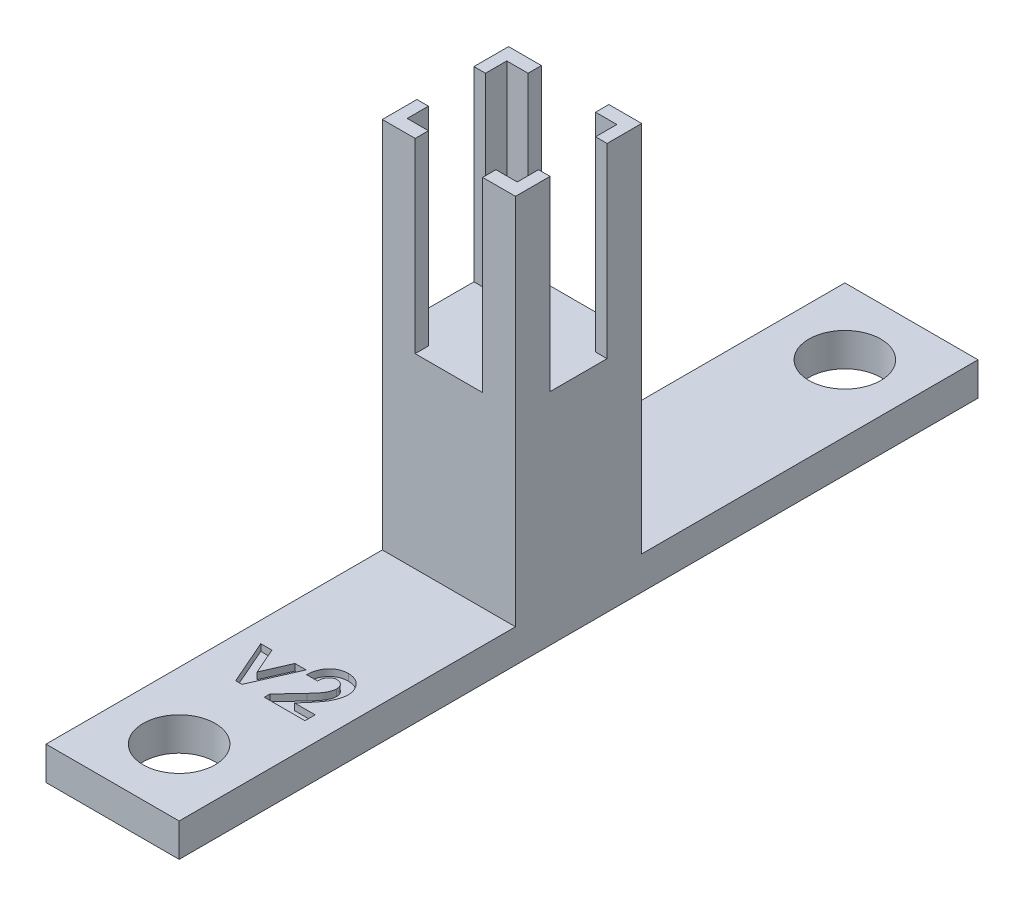
SolidWorks part; units mm, degrees
ref_plane "Front Plane" through (0, 0, 0) normal (0, 0, 1) x (1, 0, 0)
ref_plane "Top Plane" through (0, 0, 0) normal (0, 1, 0) x (1, 0, 0)
ref_plane "Right Plane" through (0, 0, 0) normal (1, 0, 0) x (0, 0, -1)
sketch "Sketch1" plane through (0, 0, 0) normal (0, 1, 0) x (1, 0, 0)
  line L0 (-5.25, 4.75) -> (-5.25, 2.718)
  line L1 (-5.25, -4.75) -> (5.25, -4.75) construction
  line L2 (-5.25, -4.75) -> (-5.25, 4.75) construction
  line L3 (-5.25, 4.75) -> (5.25, 4.75) construction
  line L4 (5.25, -4.75) -> (5.25, 4.75) construction
  line L5 (-5.25, -4.75) -> (5.25, 4.75) construction
  line L6 (-5.25, 4.75) -> (5.25, -4.75) construction
  line L7 (-5.25, 2.718) -> (-6.52, 2.718)
  line L8 (-6.52, 2.718) -> (-6.52, 6.02)
  line L9 (-6.52, 6.02) -> (-3.218, 6.02)
  line L10 (-3.218, 6.02) -> (-3.218, 4.75)
  line L11 (-3.218, 4.75) -> (-5.25, 4.75)
  line L12 (0, 4.75) -> (0, -4.75) construction
  line L13 (-5.25, 0) -> (5.25, 0) construction
  line L14 (6.52, 2.718) -> (6.52, 6.02)
  line L15 (5.25, 2.718) -> (6.52, 2.718)
  line L16 (5.25, 4.75) -> (5.25, 2.718)
  line L17 (3.218, 4.75) -> (5.25, 4.75)
  line L18 (3.218, 6.02) -> (3.218, 4.75)
  line L19 (6.52, 6.02) -> (3.218, 6.02)
  line L20 (5.25, -2.718) -> (6.52, -2.718)
  line L21 (5.25, -4.75) -> (5.25, -2.718)
  line L22 (3.218, -4.75) -> (5.25, -4.75)
  line L23 (3.218, -6.02) -> (3.218, -4.75)
  line L24 (6.52, -6.02) -> (3.218, -6.02)
  line L25 (6.52, -2.718) -> (6.52, -6.02)
  line L26 (-5.25, -2.718) -> (-6.52, -2.718)
  line L27 (-5.25, -4.75) -> (-5.25, -2.718)
  line L28 (-3.218, -4.75) -> (-5.25, -4.75)
  line L29 (-3.218, -6.02) -> (-3.218, -4.75)
  line L30 (-6.52, -6.02) -> (-3.218, -6.02)
  line L31 (-6.52, -2.718) -> (-6.52, -6.02)
  point P0 (0, 0)
  dimension "D1" = 10.5
  dimension "D2" = 9.5
  dimension "D3" = 1.27
  dimension "D4" = 2.032
extrude "Boss-Extrude1" add sketch "Sketch1" along normal blind 17.78
sketch "Sketch2" plane through (0, 0, 0) normal (0, -1, 0) x (-1, 0, 0)
  line L1 (6.52, -6.02) -> (-6.52, -6.02)
  line L2 (6.52, -6.02) -> (6.52, 6.02)
  line L3 (6.52, 6.02) -> (-6.52, 6.02)
  line L4 (-6.52, -6.02) -> (-6.52, 6.02)
extrude "Boss-Extrude2" add sketch "Sketch2" along normal blind 17.78
sketch "Sketch3" plane through (0, -17.78, 0) normal (0, -1, 0) x (-1, 0, 0)
  line L0 (0, 0) -> (6.35, 0) construction
  line L1 (-6.35, -38.1) -> (6.35, -38.1)
  line L2 (-6.35, -38.1) -> (-6.35, 38.1)
  line L3 (-6.35, 38.1) -> (6.35, 38.1)
  line L4 (6.35, -38.1) -> (6.35, 38.1)
  line L5 (-6.35, -38.1) -> (6.35, 38.1) construction
  line L6 (-6.35, 38.1) -> (6.35, -38.1) construction
  circle A0 centre (0, 31.75) radius 3.429
  circle A1 centre (0, -31.75) radius 3.429
  point P0 (0, 0)
  dimension "D2" = 6.858
  dimension "D1" = 12.7
  dimension "D3" = 31.75
  dimension "D4" = 76.2
extrude "Boss-Extrude3" add sketch "Sketch3" along normal blind 3.175
sketch "Sketch4" plane through (0, -20.955, 0) normal (0, -1, 0) x (1, 0, 0)
  line L4 (-6.35, 38.1) -> (-6.35, -38.1)
  line L5 (-6.35, -38.1) -> (6.35, -38.1)
  line L6 (6.35, -38.1) -> (6.35, 38.1)
  line L7 (6.35, 38.1) -> (-6.35, 38.1)
  line L8 (-6.35, 38.1) -> (-6.35, -38.1)
  line L9 (-6.35, -38.1) -> (6.35, -38.1)
  line L10 (6.35, -38.1) -> (6.35, 38.1)
  line L11 (6.35, 38.1) -> (-6.35, 38.1)
  dimension "D1" = 0
extrude "Cut-Extrude2" cut sketch "Sketch4" against normal through all flip side to cut
sketch "Sketch5" plane through (0, -17.78, 0) normal (0, 1, 0) x (1, 0, 0)
  line L0 (-6.35, -23.8163) -> (6.35, -23.8163) construction
  line L1 (-6.35, -38.1) -> (-6.35, -6.02) construction
  line L2 (6.35, -6.02) -> (6.35, -38.1) construction
  text T0 "<b>v2</b>" font "Century Gothic" height in points 22
extrude "Cut-Extrude3" cut sketch "Sketch5" against normal blind 0.635
